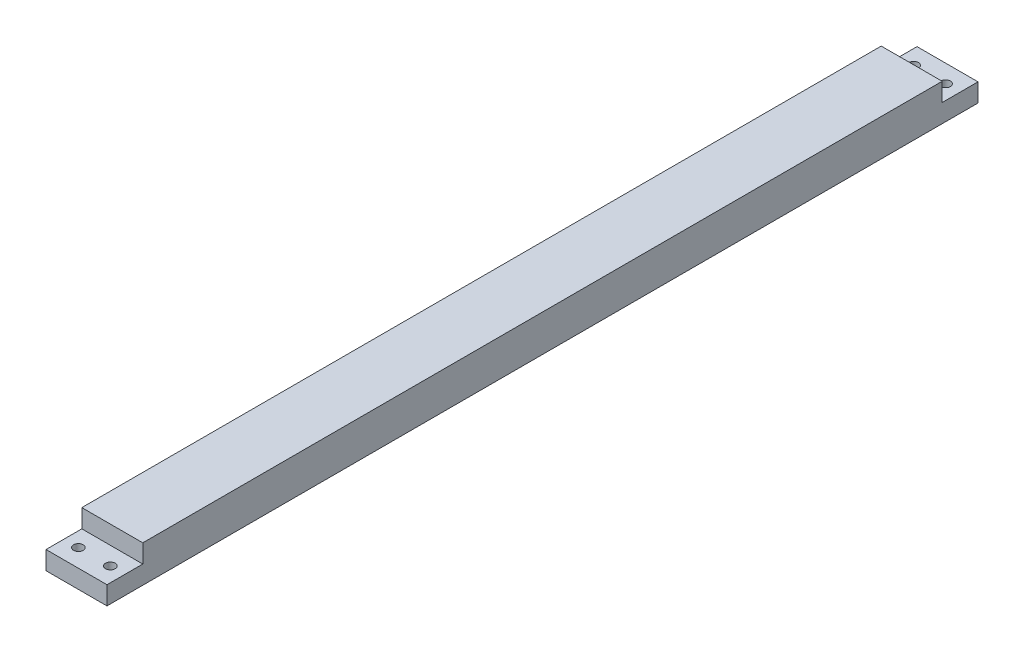
SolidWorks part; units mm, degrees
ref_plane "Front" through (0, 0, 0) normal (0, 0, 1) x (1, 0, 0)
ref_plane "Top" through (0, 0, 0) normal (0, 1, 0) x (1, 0, 0)
ref_plane "Right" through (0, 0, 0) normal (1, 0, 0) x (0, 0, -1)
sketch "Esquisse1" plane through (0, 0, 0) normal (0, 0, 1) x (1, 0, 0)
  line L1 (0, 0) -> (63, 0)
  line L2 (0, 0) -> (0, 38)
  line L3 (0, 38) -> (63, 38)
  line L4 (63, 0) -> (63, 38)
  dimension "D1" = 38
  dimension "D2" = 63
extrude "Boss.-Extru.1" add sketch "Esquisse1" along normal blind 900
sketch "Esquisse2" plane through (0, 0, 0) normal (-1, 0, 0) x (0, 0, 1)
  line L0 (450, 0) -> (450, 38) construction
  line L1 (0, 38) -> (37, 38)
  line L2 (0, 38) -> (0, 19)
  line L3 (0, 19) -> (37, 19)
  line L4 (37, 38) -> (37, 19)
  line L5 (900, 0) -> (0, 0) construction
  line L6 (900, 38) -> (0, 38) construction
  line L7 (863, 38) -> (863, 19)
  line L8 (900, 19) -> (863, 19)
  line L9 (900, 38) -> (900, 19)
  line L10 (900, 38) -> (863, 38)
  dimension "D1" = 19
  dimension "D2" = 37
extrude "Enlèv. mat.-Extru.1" cut sketch "Esquisse2" against normal through all
sketch "Esquisse3" plane through (0, 19, 0) normal (0, 1, 0) x (1, 0, 0)
  line L0 (0, -18.5) -> (63, -18.5) construction
  line L1 (0, 0) -> (0, -37) construction
  line L2 (63, 0) -> (63, -37) construction
  line L3 (31.5, -18.5) -> (31.5, 0) construction
  line L4 (63, 0) -> (0, 0) construction
  line L5 (63, -450) -> (0, -450) construction
  line L6 (63, -863) -> (63, -37) construction
  line L7 (0, -863) -> (0, -37) construction
  line L8 (31.5, -881.5) -> (31.5, -900) construction
  line L9 (0, -881.5) -> (63, -881.5) construction
  circle A0 centre (15, -18.5) radius 5
  circle A1 centre (48, -18.5) radius 5
  circle A2 centre (48, -881.5) radius 5
  circle A3 centre (15, -881.5) radius 5
  dimension "D1" = 10
  dimension "D2" = 15
extrude "Enlèv. mat.-Extru.2" cut sketch "Esquisse3" against normal through all
